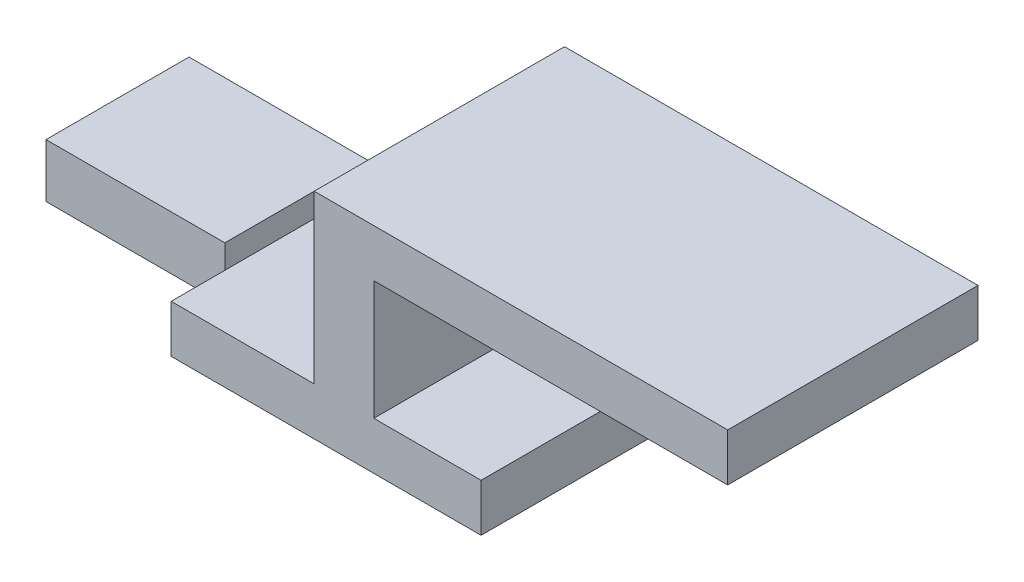
SolidWorks part; units mm, degrees
ref_plane "Front Plane" through (0, 0, 0) normal (0, 0, 1) x (1, 0, 0)
ref_plane "Top Plane" through (0, 0, 0) normal (0, 1, 0) x (1, 0, 0)
ref_plane "Right Plane" through (0, 0, 0) normal (1, 0, 0) x (0, 0, -1)
sketch "Sketch1" plane through (0, 0, 0) normal (0, 0, 1) x (1, 0, 0)
  line L0 (-18.9236, 0) -> (23.1502, 0) construction
  line L1 (4, 2) -> (4, 12)
  line L2 (-13, -2) -> (13, -2)
  line L3 (-13, -2) -> (-13, 2)
  line L4 (-13, 2) -> (-1, 2)
  line L5 (13, -2) -> (13, 2)
  line L6 (-13, -2) -> (13, 2) construction
  line L7 (-13, 2) -> (13, -2) construction
  line L8 (4, 12) -> (33.6847, 12)
  line L9 (33.6847, 12) -> (33.6847, 16)
  line L10 (33.6847, 16) -> (-1, 16)
  line L11 (-1, 16) -> (-1, 2)
  line L12 (4, 2) -> (13, 2)
  point P3 (0, 0)
  dimension "D1" = 26
  dimension "D2" = 4
  dimension "D3" = 9
  dimension "D4" = 10
  dimension "D5" = 4
  dimension "D6" = 5
extrude "Boss-Extrude2" add sketch "Sketch1" along normal blind 21
sketch "Sketch2" plane through (-13, 0, 0) normal (-1, 0, 0) x (0, 0, 1)
  line L0 (-3.0287, -0.5) -> (24.5032, -0.5) construction
  line L1 (21, -2) -> (0, -2) construction
  line L2 (0, 16) -> (0, 2) construction
  line L3 (4.5, -0.5) -> (16.5, -0.5)
  line L4 (4.5, -0.5) -> (4.5, 4)
  line L5 (4.5, 4) -> (16.5, 4)
  line L6 (16.5, -0.5) -> (16.5, 4)
  dimension "D1" = 1.5
  dimension "D2" = 12
  dimension "D3" = 4.5
  dimension "D4" = 4.5
extrude "Boss-Extrude3" add sketch "Sketch2" along normal blind 15
